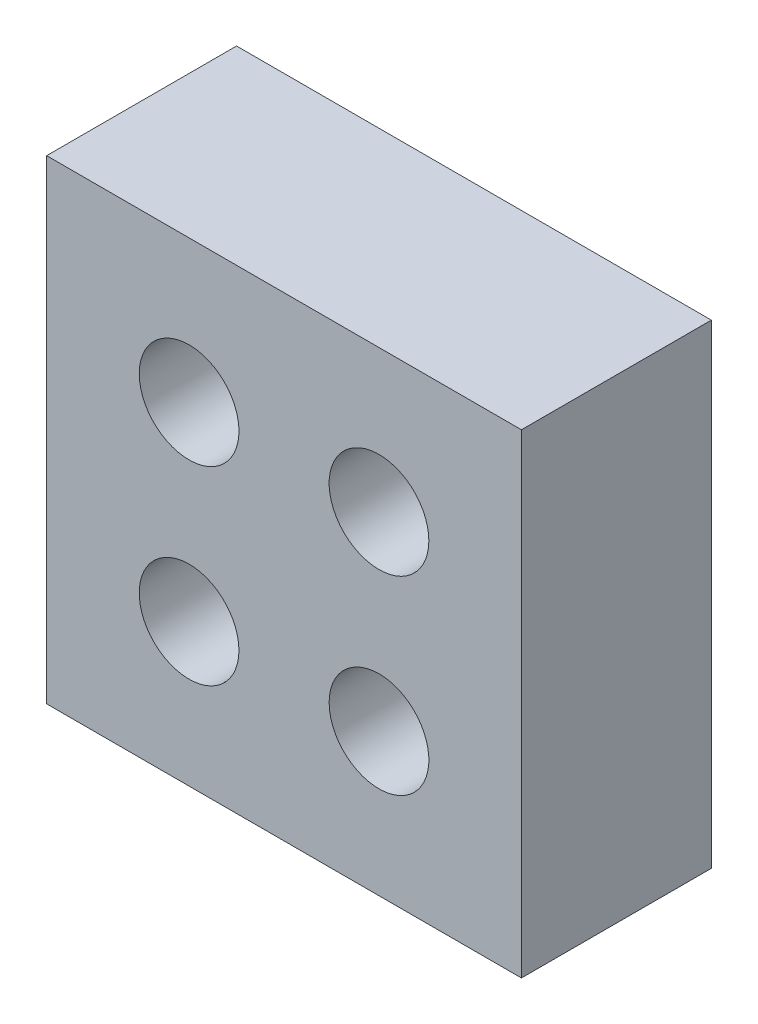
SolidWorks part; units mm, degrees
ref_plane "前视基准面" through (0, 0, 0) normal (0, 0, 1) x (1, 0, 0)
ref_plane "上视基准面" through (0, 0, 0) normal (0, 1, 0) x (1, 0, 0)
ref_plane "右视基准面" through (0, 0, 0) normal (1, 0, 0) x (0, 0, -1)
other "Configuration Table"
sketch "草图1" plane through (0, 0, 0) normal (0, 0, 1) x (1, 0, 0)
  line L1 (0, 0) -> (15, 0)
  line L2 (0, 0) -> (0, -15)
  line L3 (0, -15) -> (15, -15)
  line L4 (15, 0) -> (15, -15)
  dimension "D1" = 15
  dimension "D2" = 15
extrude "凸台-拉伸1" add sketch "草图1" along normal blind 6
sketch "草图2" plane through (0, 0, 6) normal (0, 0, 1) x (1, 0, 0)
  line L0 (0, -7.5) -> (15, -7.5) construction
  line L1 (0, 0) -> (0, -15) construction
  line L2 (15, -15) -> (15, 0) construction
  line L3 (7.5, -7.5) -> (7.5, -15) construction
  line L4 (0, -15) -> (15, -15) construction
  circle A0 centre (4.5, -10.5) radius 1.575
  circle A1 centre (10.5, -10.5) radius 1.575
  circle A2 centre (10.5, -4.5) radius 1.575
  circle A3 centre (4.5, -4.5) radius 1.575
  dimension "D1" = 3.15
  dimension "D2" = 3
  dimension "D3" = 3
extrude "切除-拉伸1" cut sketch "草图2" against normal through all
